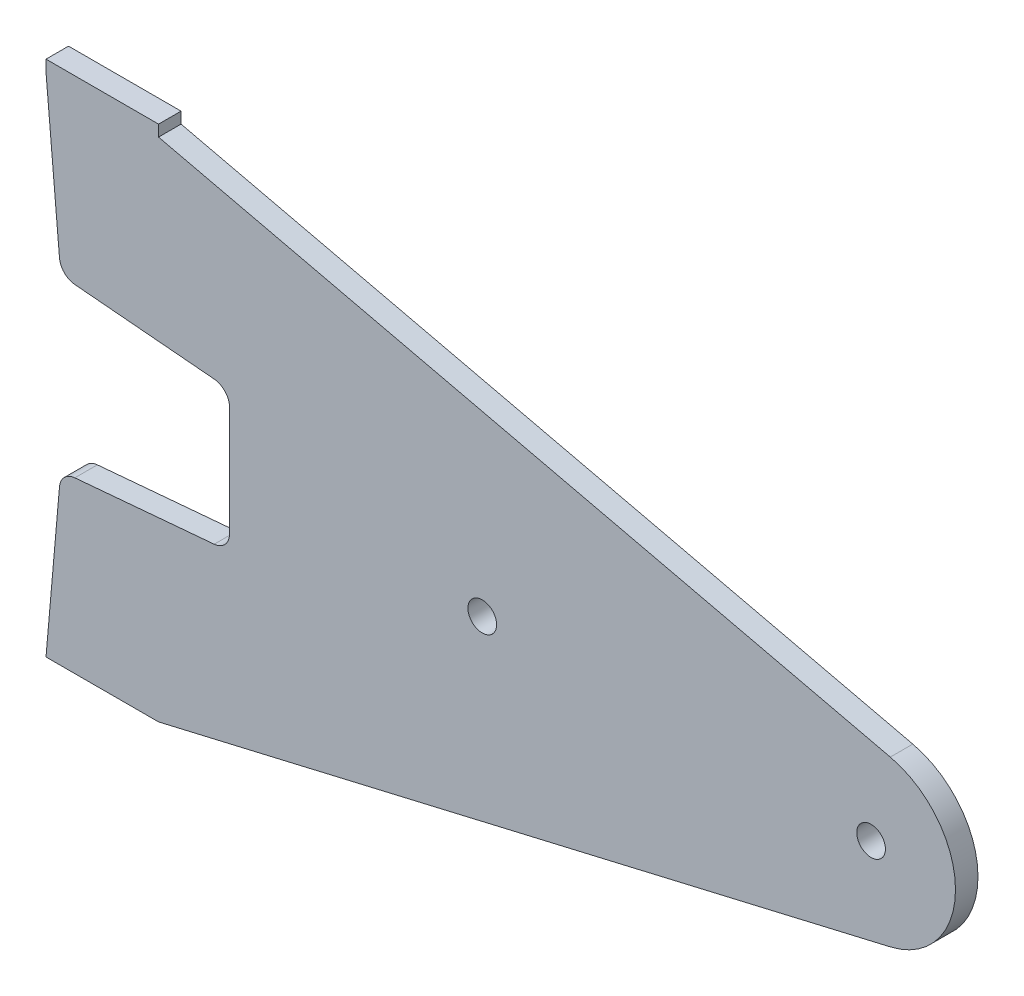
SolidWorks part; units mm, degrees
ref_plane "Front Plane" through (0, 0, 0) normal (0, 0, 1) x (1, 0, 0)
ref_plane "Top Plane" through (0, 0, 0) normal (0, 1, 0) x (1, 0, 0)
ref_plane "Right Plane" through (0, 0, 0) normal (1, 0, 0) x (0, 0, -1)
sketch "Sketch1" plane through (0, 0, 0) normal (0, 0, 1) x (1, 0, 0)
  line L0 (0, 0) -> (225, 0) construction
  line L1 (0, 0) -> (-75.9033, 0) construction
  line L2 (15, 15) -> (45, 12.375) construction
  line L3 (-45, -45) -> (45, -45) construction
  line L4 (-45, -45) -> (-45, 45) construction
  line L5 (-45, 45) -> (45, 45) construction
  line L6 (45, -45) -> (45, 45) construction
  line L7 (-45, -45) -> (45, 45) construction
  line L8 (-45, 45) -> (45, -45) construction
  line L9 (-15, -15) -> (15, -15) construction
  line L10 (-15, -15) -> (-15, 15) construction
  line L11 (-15, 15) -> (15, 15) construction
  line L12 (15, -15) -> (15, 15) construction
  line L13 (-15, -15) -> (15, 15) construction
  line L14 (-15, 15) -> (15, -15) construction
  line L15 (15, 15) -> (45, 15) construction
  line L16 (45, 45) -> (15, 15) construction
  line L17 (15, 15) -> (12.375, 45) construction
  line L18 (14.8729, 17.6) -> (12.7063, 42.3615)
  line L19 (17.6, 14.8729) -> (42.3615, 12.7063)
  line L20 (15.0923, 15.0923) -> (12.4746, 45.0087) construction
  line L21 (15.0923, 15.0923) -> (45.0087, 12.4746) construction
  line L22 (45.1, -9.7177) -> (45.1, 9.7177)
  line L23 (12.7063, 42.3615) -> (12.4746, 45.0087)
  line L24 (45.1, -45) -> (45.1, 45) construction
  line L25 (32.1293, -45.0002) -> (12.4746, -45.0087)
  line L26 (17.6, -14.8729) -> (42.3615, -12.7063)
  line L27 (14.8729, -17.6) -> (12.7063, -42.3615) construction
  line L28 (0, -45.1) -> (9.7177, -45.1) construction
  line L29 (0, 0) -> (0, 45.1) construction
  line L30 (-14.8729, 17.6) -> (-12.7063, 42.3615) construction
  line L31 (32.4746, 45) -> (162.5092, 14.6063)
  line L32 (-45, 47) -> (45, 47) construction
  line L33 (-12.7063, 42.3615) -> (-13.7896, 29.9807) construction
  line L34 (225, -45) -> (45, -45) construction
  line L35 (225, -45) -> (225, 45) construction
  line L36 (225, 45) -> (45, 45) construction
  line L37 (45, -45) -> (45, 45) construction
  line L38 (225, -45) -> (45, 45) construction
  line L39 (225, 45) -> (45, -45) construction
  line L40 (12.4746, 45.0087) -> (12.4746, 47)
  line L41 (12.4746, 47) -> (32.4746, 47)
  line L44 (14.8729, -17.6) -> (12.7063, -42.3615)
  line L46 (12.7063, -42.3615) -> (12.4746, -45.0087)
  line L47 (32.4746, 47) -> (32.4746, 45)
  line L48 (32.8108, -44.9214) -> (162.5092, -14.6063)
  line L49 (174.0952, 0) -> (45.1, 0) construction
  arc A0 (14.8729, 17.6) -> (17.6, 14.8729) centre (17.8615, 17.8615) ccw
  arc A1 (42.3615, 12.7063) -> (45.1, 9.7177) centre (42.1, 9.7177) cw
  arc A2 (162.5092, 14.6063) -> (162.5092, -14.6063) centre (159.0952, 0) cw
  arc A3 (42.3615, -12.7063) -> (45.1, -9.7177) centre (42.1, -9.7177) ccw
  arc A4 (14.8729, -17.6) -> (17.6, -14.8729) centre (17.8615, -17.8615) cw
  arc A5 (12.7063, -42.3615) -> (9.7177, -45.1) centre (9.7177, -42.1) cw construction
  arc A6 (-12.7063, 42.3615) -> (-9.7177, 45.1) centre (-9.7177, 42.1) cw construction
  circle A7 centre (159.0952, 0) radius 2.55
  circle A8 centre (90, 0) radius 2.55
  arc A9 (32.1293, -45.0002) -> (32.8108, -44.9214) centre (32.128, -42.0002) ccw
  point P28 (135, 0)
  point P33 (45.1, 0)
  point P51 (32.4746, -45)
  dimension "D5" = 3
  dimension "D7" = 3
  dimension "D9" = 2
  dimension "D10" = 20
  dimension "D11" = 15
  dimension "D12" = 5.1
  dimension "D13" = 90
  dimension "D14" = 3
  dimension "D1" = 90
  dimension "D2" = 0.1
  dimension "D3" = 30
  dimension "D4" = 2.625
  dimension "D8" = 180
  dimension "D6" = 0.1
extrude "Boss-Extrude1" add sketch "Sketch1" along normal blind 4
